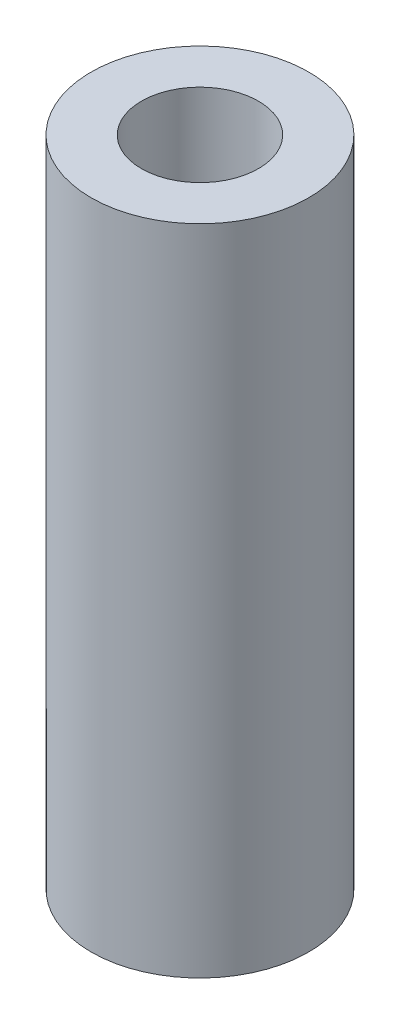
SolidWorks part; units mm, degrees
ref_plane "前视基准面" through (0, 0, 0) normal (0, 0, 1) x (1, 0, 0)
ref_plane "上视基准面" through (0, 0, 0) normal (0, 1, 0) x (1, 0, 0)
ref_plane "右视基准面" through (0, 0, 0) normal (1, 0, 0) x (0, 0, -1)
other "Configuration Table"
sketch "草图1" plane through (0, 0, 0) normal (0, 1, 0) x (1, 0, 0)
  circle A0 centre (0, 0) radius 2.15
  circle A1 centre (0, 0) radius 4
  dimension "D1" = 4.3
  dimension "D2" = 8
extrude "凸台-拉伸1" add sketch "草图1" along normal blind 24
